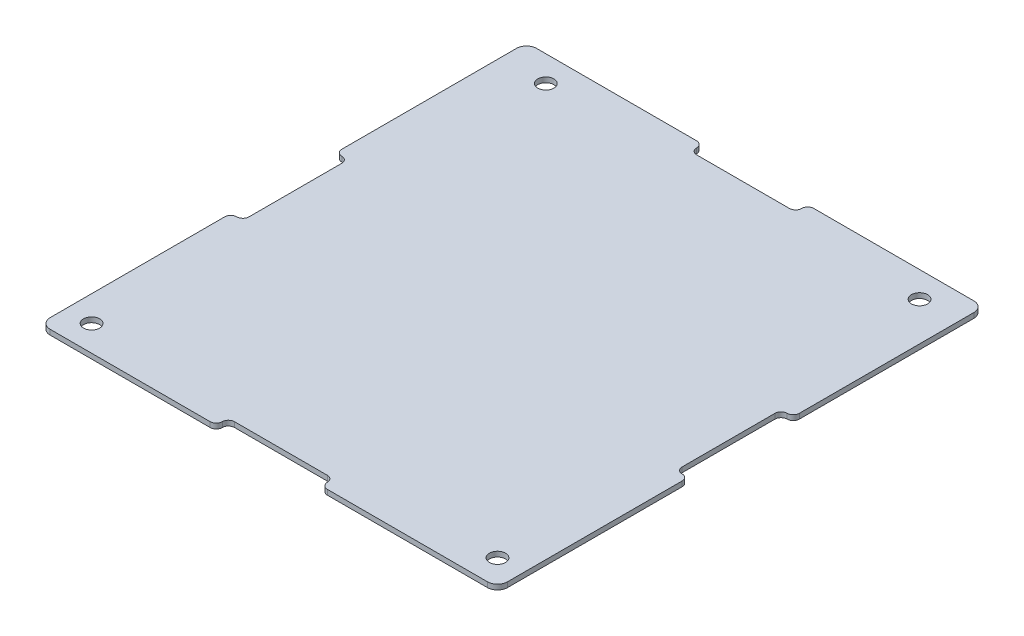
SolidWorks part; units mm, degrees
ref_plane "Front" through (0, 0, 0) normal (0, 0, 1) x (1, 0, 0)
ref_plane "Top" through (0, 0, 0) normal (0, 1, 0) x (1, 0, 0)
ref_plane "Right" through (0, 0, 0) normal (1, 0, 0) x (0, 0, -1)
sketch "Эскиз1" plane through (0, 0, 0) normal (0, 1, 0) x (1, 0, 0)
  line L0 (-45.085, -11.55) -> (-45.085, -45.945)
  line L1 (-43.0844, -47.9456) -> (-11.5494, -47.9456)
  line L2 (-9.1494, -45.5456) -> (9.1506, -45.5456)
  line L3 (11.5506, -47.9456) -> (43.0856, -47.9456)
  line L4 (45.085, -45.9462) -> (45.085, -11.55)
  line L5 (42.685, -9.15) -> (42.685, 9.15)
  line L6 (45.085, 11.55) -> (45.085, 45.945)
  line L7 (43.085, 47.945) -> (11.55, 47.945)
  line L8 (9.15, 45.545) -> (-9.15, 45.545)
  line L9 (-11.55, 47.945) -> (-43.085, 47.945)
  line L10 (-45.085, 45.945) -> (-45.085, 11.55)
  line L11 (-42.685, 9.15) -> (-42.685, -9.15)
  line L12 (-42.685, 0) -> (42.685, 0) construction
  line L13 (0.0006, -45.5456) -> (0, 45.545) construction
  circle A0 centre (37.465, 42.865) radius 1.59
  circle A1 centre (40.005, -42.865) radius 1.59
  circle A2 centre (-40.005, -42.865) radius 1.59
  circle A3 centre (-36.195, 42.865) radius 1.59
  arc A4 (-45.085, 45.945) -> (-43.085, 47.945) centre (-43.085, 45.945) cw
  arc A5 (-10.35, 46.745) -> (-11.55, 47.945) centre (-11.55, 46.745) ccw
  arc A6 (-10.35, 46.745) -> (-9.15, 45.545) centre (-9.15, 46.745) ccw
  arc A7 (10.35, 46.745) -> (9.15, 45.545) centre (9.15, 46.745) cw
  arc A8 (10.35, 46.745) -> (11.55, 47.945) centre (11.55, 46.745) cw
  arc A9 (10.3506, -46.7456) -> (11.5506, -47.9456) centre (11.5506, -46.7456) ccw
  arc A10 (10.3506, -46.7456) -> (9.1506, -45.5456) centre (9.1506, -46.7456) ccw
  arc A11 (-10.3494, -46.7456) -> (-9.1494, -45.5456) centre (-9.1494, -46.7456) cw
  arc A12 (-10.3494, -46.7456) -> (-11.5494, -47.9456) centre (-11.5494, -46.7456) cw
  arc A13 (-45.085, 11.55) -> (-43.885, 10.35) centre (-43.885, 11.55) ccw
  arc A14 (-42.685, 9.15) -> (-43.885, 10.35) centre (-43.885, 9.15) ccw
  arc A15 (-42.685, -9.15) -> (-43.885, -10.35) centre (-43.885, -9.15) cw
  arc A16 (-45.085, -11.55) -> (-43.885, -10.35) centre (-43.885, -11.55) cw
  arc A17 (45.085, -11.55) -> (43.885, -10.35) centre (43.885, -11.55) ccw
  arc A18 (42.685, -9.15) -> (43.885, -10.35) centre (43.885, -9.15) ccw
  arc A19 (42.685, 9.15) -> (43.885, 10.35) centre (43.885, 9.15) cw
  arc A20 (45.085, 11.55) -> (43.885, 10.35) centre (43.885, 11.55) cw
  arc A21 (43.085, 47.945) -> (45.085, 45.945) centre (43.085, 45.945) cw
  arc A22 (-45.085, -45.945) -> (-43.0844, -47.9456) centre (-43.0844, -45.945) ccw
  arc A23 (43.0856, -47.9456) -> (45.085, -45.9462) centre (43.0856, -45.9462) ccw
extrude "Бобышка-Вытянуть1" add sketch "Эскиз1" along normal blind 1
